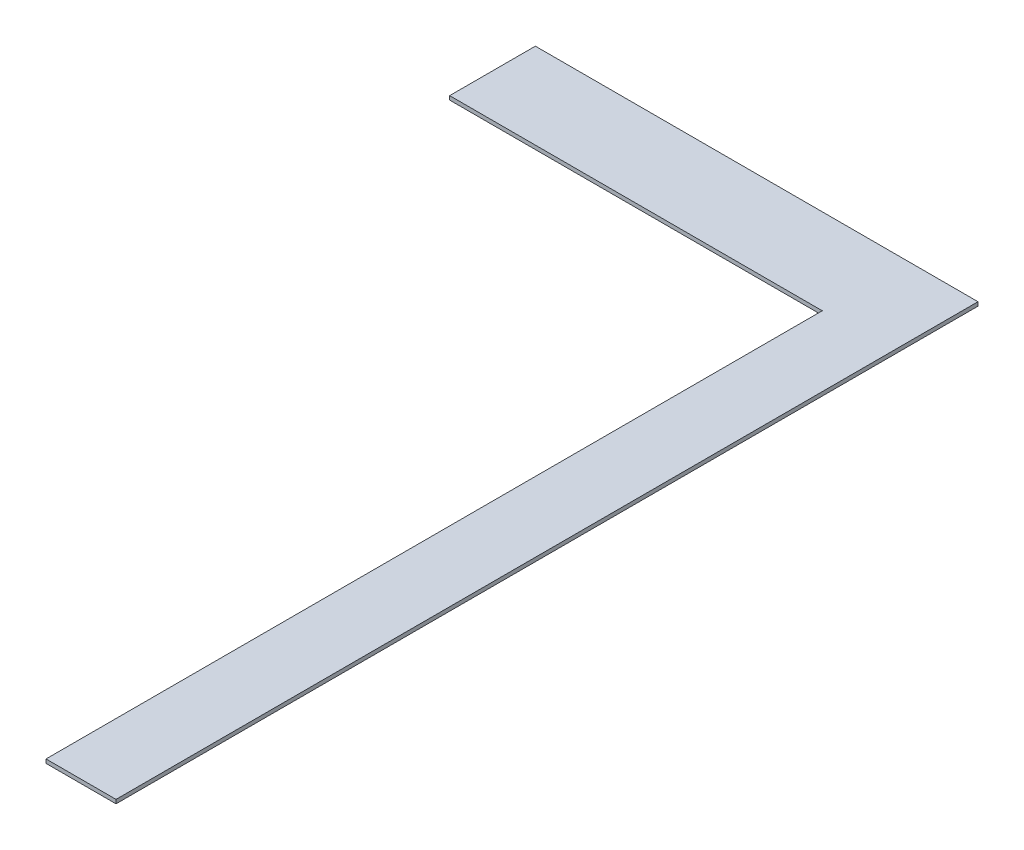
SolidWorks part; units mm, degrees
material "Гипс"
ref_plane "Спереди" through (0, 0, 0) normal (0, 0, 1) x (1, 0, 0)
ref_plane "Сверху" through (0, 0, 0) normal (0, 1, 0) x (1, 0, 0)
ref_plane "Справа" through (0, 0, 0) normal (1, 0, 0) x (0, 0, -1)
sketch "Эскиз1" plane through (0, 0, 0) normal (0, 1, 0) x (1, 0, 0)
  line L0 (-225.5, -276) -> (-225.5, -2776) construction
  line L1 (-1425.5, -276) -> (-225.5, -276) construction
  line L2 (-225.5, -276) -> (-225.5, -2776)
  line L3 (-1425.5, -276) -> (-225.5, -276)
  line L4 (-1425.5, -276) -> (-1425.5, 0)
  line L5 (-1425.5, -1) -> (-1425.5, -376) construction
  line L7 (-1425.5, 0) -> (0, 0)
  line L8 (0, 0) -> (0, -2776)
  line L9 (0, -2776) -> (-225.5, -2776)
  point P10 (-2587.2644, 149.9685)
  point P12 (0, 0)
extrude "Бобышка-Вытянуть1" add sketch "Эскиз1" against normal blind 12.5
